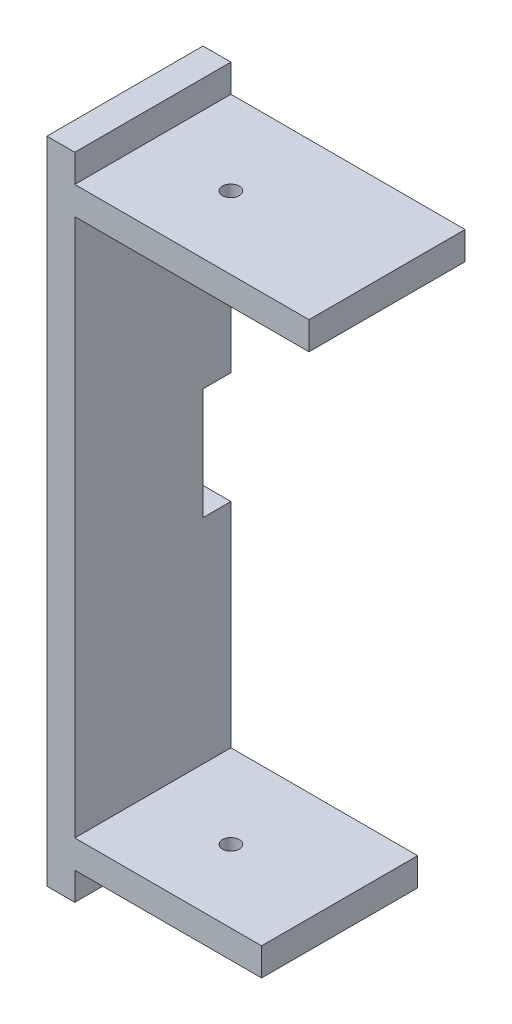
SolidWorks part; units mm, degrees
ref_plane "前基準面" through (0, 0, 0) normal (0, 0, 1) x (1, 0, 0)
ref_plane "上基準面" through (0, 0, 0) normal (0, 1, 0) x (1, 0, 0)
ref_plane "右基準面" through (0, 0, 0) normal (1, 0, 0) x (0, 0, -1)
sketch "草圖1" plane through (0, 0, 0) normal (0, 0, 1) x (1, 0, 0)
  line L0 (-17.4514, -6.1961) -> (-17.4514, -11.1961)
  line L1 (-22.4514, 105.3039) -> (-17.4514, 105.3039)
  line L2 (-22.4514, 105.3039) -> (-22.4514, -11.1961)
  line L3 (-22.4514, -11.1961) -> (-17.4514, -11.1961)
  line L4 (-17.4514, 105.3039) -> (-17.4514, 100.3039)
  line L5 (-17.4514, -6.1961) -> (16.0486, -6.1961)
  line L6 (-17.4514, 95.3039) -> (-17.4514, -1.1961)
  line L7 (-17.4514, -1.1961) -> (16.0486, -1.1961)
  line L8 (16.0486, -6.1961) -> (16.0486, -1.1961)
  line L9 (-17.4514, 100.3039) -> (24.5486, 100.3039)
  line L11 (-17.4514, 95.3039) -> (24.5486, 95.3039)
  line L12 (24.5486, 100.3039) -> (24.5486, 95.3039)
  dimension "D1" = 5
  dimension "D2" = 5
  dimension "D3" = 33.5
  dimension "D4" = 116.5
  dimension "D5" = 5
  dimension "D6" = 5
  dimension "D7" = 42
  dimension "D8" = 5
extrude "填料-伸長1" add sketch "草圖1" along normal blind 28
sketch "草圖2" plane through (0, 0, 0) normal (0, 0, -1) x (-1, 0, 0)
  line L0 (17.4514, 100.3039) -> (17.4514, 105.3039) construction
  line L1 (17.4514, 37.0539) -> (22.4514, 37.0539)
  line L2 (17.4514, 37.0539) -> (17.4514, 57.0539)
  line L3 (17.4514, 57.0539) -> (22.4514, 57.0539)
  line L4 (22.4514, 37.0539) -> (22.4514, 57.0539)
  line L5 (22.4514, 105.3039) -> (22.4514, -11.1961) construction
  line L6 (17.4514, 105.3039) -> (22.4514, 105.3039) construction
  dimension "D1" = 20
  dimension "D2" = 48.25
extrude "除料-伸長1" cut sketch "草圖2" against normal blind 5
sketch "草圖3" plane through (0, -6.1961, 0) normal (0, -1, 0) x (1, 0, 0)
  line L0 (-17.4514, 0) -> (16.0486, 0) construction
  line L2 (-17.4514, 28) -> (-17.4514, 0) construction
  circle A0 centre (-2.4514, 15) radius 1.5
  dimension "D1" = 3
  dimension "D2" = 15
  dimension "D3" = 15
extrude "除料-伸長2" cut sketch "草圖3" against normal through all contours A0
